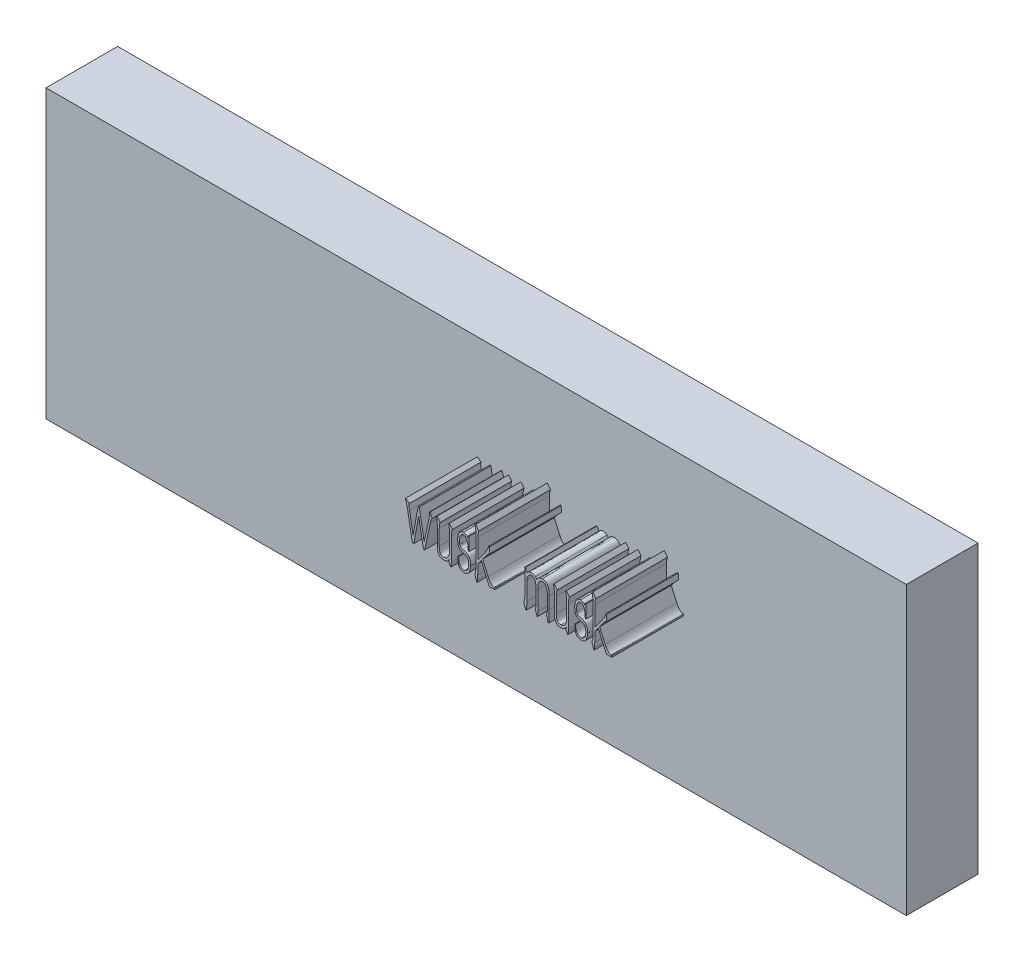
SolidWorks part; units mm, degrees
ref_plane "前视基准面" through (0, 0, 0) normal (0, 0, 1) x (1, 0, 0)
ref_plane "上视基准面" through (0, 0, 0) normal (0, 1, 0) x (1, 0, 0)
ref_plane "右视基准面" through (0, 0, 0) normal (1, 0, 0) x (0, 0, -1)
other "Configuration Table"
sketch "草图1" plane through (0, 0, 0) normal (0, 0, 1) x (1, 0, 0)
  line L1 (-30, -10) -> (30, -10)
  line L2 (-30, -10) -> (-30, 10)
  line L3 (-30, 10) -> (30, 10)
  line L4 (30, -10) -> (30, 10)
  line L5 (-30, -10) -> (30, 10) construction
  line L6 (-30, 10) -> (30, -10) construction
  point P0 (0, 0)
extrude "凸台-拉伸1" add sketch "草图1" along normal blind 5
sketch "草图2" plane through (0, 0, 5) normal (0, 0, 1) x (1, 0, 0)
  line L0 (-8.1, 0) -> (8.1, 0) construction
  text T0 "wusk musk" font "汉仪长仿宋体" height 3.5
extrude "凸台-拉伸2" add sketch "草图2" along normal blind 5
